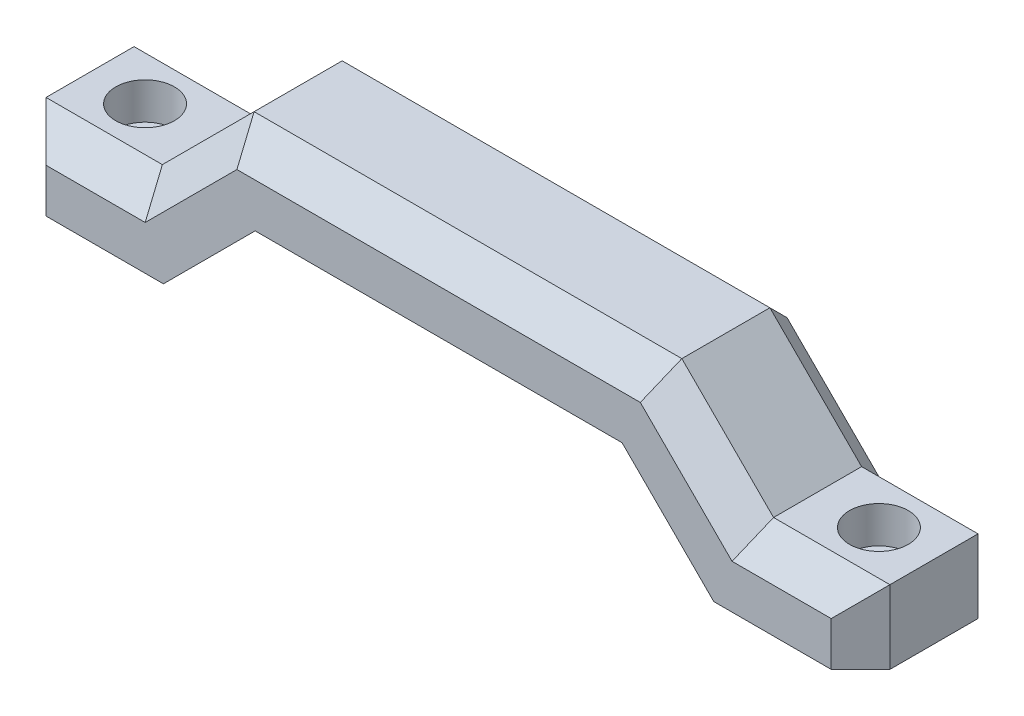
SolidWorks part; units mm, degrees
ref_plane "Front Plane" through (0, 0, 0) normal (0, 0, 1) x (1, 0, 0)
ref_plane "Top Plane" through (0, 0, 0) normal (0, 1, 0) x (1, 0, 0)
ref_plane "Right Plane" through (0, 0, 0) normal (1, 0, 0) x (0, 0, -1)
sketch "Sketch1" plane through (0, 0, 0) normal (0, 0, 1) x (1, 0, 0)
  line L0 (-25, 0) -> (25, 0)
  line L1 (-25, 0) -> (-37.5, -12.5)
  line L2 (-37.5, -12.5) -> (-57.5, -12.5)
  line L3 (25, 0) -> (37.5, -12.5)
  line L4 (37.5, -12.5) -> (57.5, -12.5)
  line L5 (-41.6421, -2.5) -> (-57.5, -2.5)
  line L6 (-29.1421, 10) -> (-41.6421, -2.5)
  line L7 (-29.1421, 10) -> (29.1421, 10)
  line L8 (29.1421, 10) -> (41.6421, -2.5)
  line L9 (41.6421, -2.5) -> (57.5, -2.5)
  line L10 (-57.5, -2.5) -> (-57.5, -12.5)
  line L11 (57.5, -2.5) -> (57.5, -12.5)
  line L12 (-37.5, -12.5) -> (37.5, -12.5) construction
  dimension "D1" = 45
  dimension "D2" = 50
  dimension "D3" = 45
  dimension "D4" = 115
  dimension "D5" = 20
  dimension "D6" = 10
extrude "Boss-Extrude1" add sketch "Sketch1" along normal blind 20
chamfer "Chamfer1" distance 4 angle 45 14 edges at (-49.5711, -2.5, 0) (-35.3921, 3.75, 0) (0, 10, 0) (35.3921, 3.75, 0) (49.5711, -2.5, 0) (49.5711, -2.5, 20) (35.3921, 3.75, 20) (-49.5711, -2.5, 20) (-35.3921, 3.75, 20) (0, 10, 20) (-57.5, -7.5, 0) (57.5, -7.5, 0) (57.5, -7.5, 20) (-57.5, -7.5, 20)
sketch "Sketch2" plane through (0, -2.5, 0) normal (0, 1, 0) x (1, 0, 0)
  line L0 (-50, -10) -> (50, -10) construction
  line L1 (0, -10) -> (0, 0) construction
  circle A0 centre (-50, -10) radius 1.75
  circle A1 centre (50, -10) radius 1.75
  dimension "D3" = 3.5
  dimension "D1" = 10
  dimension "D2" = 100
extrude "Cut-Extrude1" cut sketch "Sketch2" against normal through all
sketch "Sketch3" plane through (0, -2.5, 0) normal (0, 1, 0) x (1, 0, 0)
  circle A0 centre (-50, -10) radius 4
  circle A1 centre (50, -10) radius 4
  dimension "D1" = 8
extrude "Cut-Extrude2" cut sketch "Sketch3" against normal blind 5
